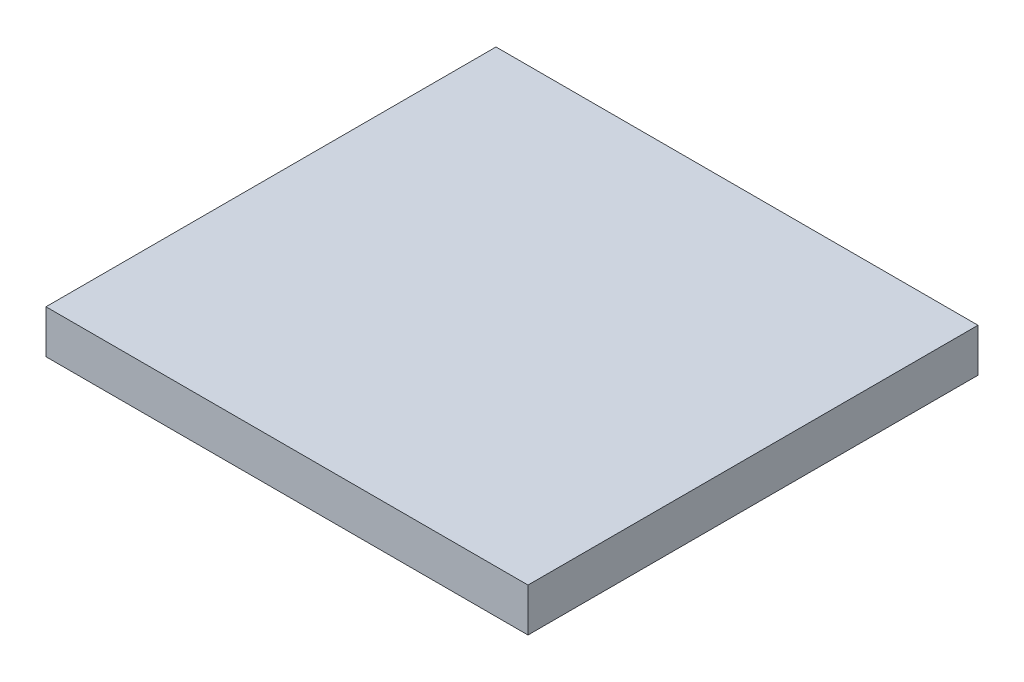
SolidWorks part; units mm, degrees
ref_plane "Front Plane" through (0, 0, 0) normal (0, 0, 1) x (1, 0, 0)
ref_plane "Top Plane" through (0, 0, 0) normal (0, 1, 0) x (1, 0, 0)
ref_plane "Right Plane" through (0, 0, 0) normal (1, 0, 0) x (0, 0, -1)
sketch "Sketch1" plane through (0, 0, 0) normal (0, 1, 0) x (1, 0, 0)
  line L1 (-53.8137, 65.8304) -> (149.3863, 65.8304)
  line L2 (-53.8137, 65.8304) -> (-53.8137, -123.8759)
  line L3 (-53.8137, -123.8759) -> (149.3863, -123.8759)
  line L4 (149.3863, 65.8304) -> (149.3863, -123.8759)
  line L5 (-53.8137, 65.8304) -> (149.3863, -123.8759) construction
  line L6 (-53.8137, -123.8759) -> (149.3863, 65.8304) construction
  point P0 (47.7863, -29.0227)
  dimension "D1" = 189.7062
  dimension "D2" = 203.2
extrude "Boss-Extrude1" add sketch "Sketch1" along normal blind 18.2562 contours L2 L1 L4 L3
